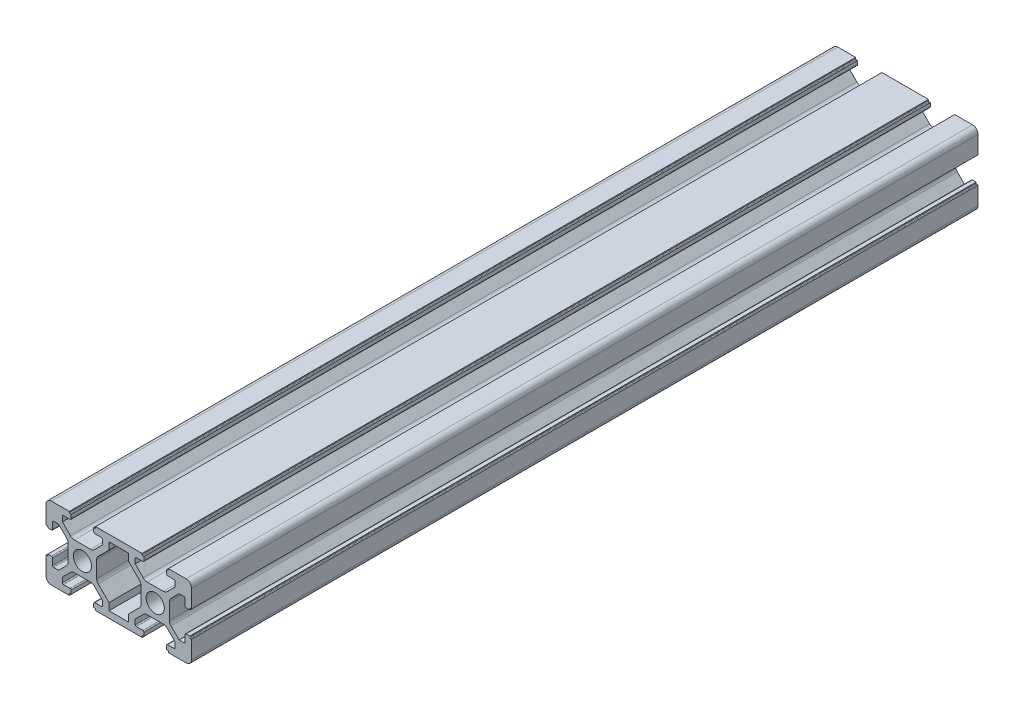
SolidWorks part; units mm, degrees
ref_plane "前视基准面" through (0, 0, 0) normal (0, 0, 1) x (1, 0, 0)
ref_plane "上视基准面" through (0, 0, 0) normal (0, 1, 0) x (1, 0, 0)
ref_plane "右视基准面" through (0, 0, 0) normal (1, 0, 0) x (0, 0, -1)
sketch "草图1" plane through (0, 0, 0) normal (0, 0, 1) x (1, 0, 0)
  line L0 (-1.9716, -6.6942) -> (-4.9322, -3.7335)
  line L1 (-5.3716, -2.6729) -> (-5.3716, 1.7645)
  line L2 (-4.9322, 2.8251) -> (-1.9716, 5.7858)
  line L3 (-0.7716, 9.5458) -> (-5.6716, 9.5458)
  line L4 (-5.6716, 9.5458) -> (-5.6716, 9.2458)
  line L5 (-5.8716, 9.0458) -> (-6.1716, 9.0458)
  line L6 (-6.1716, 9.0458) -> (-6.1716, 8.0458)
  line L7 (-5.8716, 7.7458) -> (-4.0716, 7.7458)
  line L8 (-3.7716, 7.4458) -> (-3.7716, 6.1058)
  line L9 (-3.7716, 6.1058) -> (-5.9922, 3.8851)
  line L10 (-7.0529, 3.4458) -> (-11.4903, 3.4458)
  line L11 (-12.5509, 3.8851) -> (-14.7716, 6.1058)
  line L12 (-14.7716, 6.1058) -> (-14.7716, 7.4458)
  line L13 (-14.4716, 7.7458) -> (-12.6716, 7.7458)
  line L14 (-12.3716, 8.0458) -> (-12.3716, 9.0458)
  line L15 (-12.3716, 9.0458) -> (-12.6716, 9.0458)
  line L16 (-12.8716, 9.2458) -> (-12.8716, 9.5458)
  line L17 (-12.8716, 9.5458) -> (-17.7716, 9.5458)
  line L18 (-19.2716, 8.0458) -> (-19.2716, 3.1458)
  line L19 (-19.2716, 3.1458) -> (-18.9716, 3.1458)
  line L20 (-18.7716, 2.9458) -> (-18.7716, 2.6458)
  line L21 (-18.7716, 2.6458) -> (-17.7716, 2.6458)
  line L22 (-17.4716, 2.9458) -> (-17.4716, 4.7458)
  line L23 (-17.1716, 5.0458) -> (-15.8316, 5.0458)
  line L24 (-15.8316, 5.0458) -> (-13.6109, 2.8251)
  line L25 (-13.1716, 1.7645) -> (-13.1716, -2.6729)
  line L26 (-13.6109, -3.7335) -> (-15.8316, -5.9542)
  line L27 (-15.8316, -5.9542) -> (-17.1716, -5.9542)
  line L28 (-17.4716, -5.6542) -> (-17.4716, -3.8542)
  line L29 (-17.7716, -3.5542) -> (-18.7716, -3.5542)
  line L30 (-18.7716, -3.5542) -> (-18.7716, -3.8542)
  line L31 (-18.9716, -4.0542) -> (-19.2716, -4.0542)
  line L32 (-19.2716, -4.0542) -> (-19.2716, -8.9542)
  line L33 (-17.7716, -10.4542) -> (-12.8716, -10.4542)
  line L34 (-12.8716, -10.4542) -> (-12.8716, -10.1542)
  line L35 (-12.6716, -9.9542) -> (-12.3716, -9.9542)
  line L36 (-12.3716, -9.9542) -> (-12.3716, -8.9542)
  line L37 (-12.6716, -8.6542) -> (-14.4716, -8.6542)
  line L38 (-14.7716, -8.3542) -> (-14.7716, -7.0142)
  line L39 (-14.7716, -7.0142) -> (-12.5509, -4.7935)
  line L40 (-11.4903, -4.3542) -> (-7.0529, -4.3542)
  line L41 (-5.9922, -4.7935) -> (-3.7716, -7.0142)
  line L42 (-3.7716, -7.0142) -> (-3.7716, -8.3542)
  line L43 (-4.0716, -8.6542) -> (-5.8716, -8.6542)
  line L44 (-6.1716, -8.9542) -> (-6.1716, -9.9542)
  line L45 (-6.1716, -9.9542) -> (-5.8716, -9.9542)
  line L46 (-5.6716, -10.1542) -> (-5.6716, -10.4542)
  line L47 (-5.6716, -10.4542) -> (-0.7716, -10.4542)
  line L48 (-0.7716, -10.4542) -> (7.1284, -10.4542)
  line L49 (7.1284, -10.4542) -> (7.1284, -10.1542)
  line L50 (7.3284, -9.9542) -> (7.6284, -9.9542)
  line L51 (7.6284, -9.9542) -> (7.6284, -8.9542)
  line L52 (7.3284, -8.6542) -> (5.5284, -8.6542)
  line L53 (5.2284, -8.3542) -> (5.2284, -7.0142)
  line L54 (5.2284, -7.0142) -> (7.4491, -4.7935)
  line L55 (8.5097, -4.3542) -> (12.9471, -4.3542)
  line L56 (14.0078, -4.7935) -> (16.2284, -7.0142)
  line L57 (16.2284, -7.0142) -> (16.2284, -8.3542)
  line L58 (15.9284, -8.6542) -> (14.1284, -8.6542)
  line L59 (13.8284, -8.9542) -> (13.8284, -9.9542)
  line L60 (13.8284, -9.9542) -> (14.1284, -9.9542)
  line L61 (14.3284, -10.1542) -> (14.3284, -10.4542)
  line L62 (14.3284, -10.4542) -> (19.2284, -10.4542)
  line L63 (20.7284, -8.9542) -> (20.7284, -4.0542)
  line L64 (20.7284, -4.0542) -> (20.4284, -4.0542)
  line L65 (20.2284, -3.8542) -> (20.2284, -3.5542)
  line L66 (20.2284, -3.5542) -> (19.2284, -3.5542)
  line L67 (18.9284, -3.8542) -> (18.9284, -5.6542)
  line L68 (18.6284, -5.9542) -> (17.2884, -5.9542)
  line L69 (17.2884, -5.9542) -> (15.0678, -3.7335)
  line L70 (14.6284, -2.6729) -> (14.6284, 1.7645)
  line L71 (15.0678, 2.8251) -> (17.2884, 5.0458)
  line L72 (17.2884, 5.0458) -> (18.6284, 5.0458)
  line L73 (18.9284, 4.7458) -> (18.9284, 2.9458)
  line L74 (19.2284, 2.6458) -> (20.2284, 2.6458)
  line L75 (20.2284, 2.6458) -> (20.2284, 2.9458)
  line L76 (20.4284, 3.1458) -> (20.7284, 3.1458)
  line L77 (20.7284, 3.1458) -> (20.7284, 8.0458)
  line L78 (19.2284, 9.5458) -> (14.3284, 9.5458)
  line L79 (14.3284, 9.5458) -> (14.3284, 9.2458)
  line L80 (14.1284, 9.0458) -> (13.8284, 9.0458)
  line L81 (13.8284, 9.0458) -> (13.8284, 8.0458)
  line L82 (14.1284, 7.7458) -> (15.9284, 7.7458)
  line L83 (16.2284, 7.4458) -> (16.2284, 6.1058)
  line L84 (16.2284, 6.1058) -> (14.0078, 3.8851)
  line L85 (12.9471, 3.4458) -> (8.5097, 3.4458)
  line L86 (7.4491, 3.8851) -> (5.2284, 6.1058)
  line L87 (5.2284, 6.1058) -> (5.2284, 7.4458)
  line L88 (5.5284, 7.7458) -> (7.3284, 7.7458)
  line L89 (7.6284, 8.0458) -> (7.6284, 9.0458)
  line L90 (7.6284, 9.0458) -> (7.3284, 9.0458)
  line L91 (7.1284, 9.2458) -> (7.1284, 9.5458)
  line L92 (7.1284, 9.5458) -> (2.2284, 9.5458)
  line L93 (3.4284, 5.7858) -> (6.3891, 2.8251)
  line L94 (6.8284, 1.7645) -> (6.8284, -2.6729)
  line L95 (6.3891, -3.7335) -> (3.4284, -6.6942)
  line L96 (-0.7716, 9.5458) -> (2.2284, 9.5458)
  line L99 (-1.9716, 7.7458) -> (3.4284, 7.7458)
  line L100 (3.4284, 7.7458) -> (3.4284, 5.7858)
  line L101 (-1.9716, 7.7458) -> (-1.9716, 5.7858)
  line L102 (-1.9716, -8.6542) -> (3.4284, -8.6542)
  line L103 (3.4284, -8.6542) -> (3.4284, -6.6942)
  line L104 (-1.9716, -8.6542) -> (-1.9716, -6.6942)
  arc A1 (-5.3716, -2.6729) -> (-4.9322, -3.7335) centre (-3.8716, -2.6729) ccw
  arc A2 (-4.9322, 2.8251) -> (-5.3716, 1.7645) centre (-3.8716, 1.7645) ccw
  arc A3 (-5.8716, 9.0458) -> (-5.6716, 9.2458) centre (-5.8716, 9.2458) ccw
  arc A4 (-6.1716, 8.0458) -> (-5.8716, 7.7458) centre (-5.8716, 8.0458) ccw
  arc A5 (-3.7716, 7.4458) -> (-4.0716, 7.7458) centre (-4.0716, 7.4458) ccw
  arc A6 (-7.0529, 3.4458) -> (-5.9922, 3.8851) centre (-7.0529, 4.9458) ccw
  arc A7 (-12.5509, 3.8851) -> (-11.4903, 3.4458) centre (-11.4903, 4.9458) ccw
  arc A8 (-14.4716, 7.7458) -> (-14.7716, 7.4458) centre (-14.4716, 7.4458) ccw
  arc A9 (-12.6716, 7.7458) -> (-12.3716, 8.0458) centre (-12.6716, 8.0458) ccw
  arc A10 (-12.8716, 9.2458) -> (-12.6716, 9.0458) centre (-12.6716, 9.2458) ccw
  arc A11 (-17.7716, 9.5458) -> (-19.2716, 8.0458) centre (-17.7716, 8.0458) ccw
  arc A12 (-18.7716, 2.9458) -> (-18.9716, 3.1458) centre (-18.9716, 2.9458) ccw
  arc A13 (-17.7716, 2.6458) -> (-17.4716, 2.9458) centre (-17.7716, 2.9458) ccw
  arc A14 (-17.1716, 5.0458) -> (-17.4716, 4.7458) centre (-17.1716, 4.7458) ccw
  arc A15 (-13.1716, 1.7645) -> (-13.6109, 2.8251) centre (-14.6716, 1.7645) ccw
  arc A16 (-13.6109, -3.7335) -> (-13.1716, -2.6729) centre (-14.6716, -2.6729) ccw
  arc A17 (-17.4716, -5.6542) -> (-17.1716, -5.9542) centre (-17.1716, -5.6542) ccw
  arc A18 (-17.4716, -3.8542) -> (-17.7716, -3.5542) centre (-17.7716, -3.8542) ccw
  arc A19 (-18.9716, -4.0542) -> (-18.7716, -3.8542) centre (-18.9716, -3.8542) ccw
  arc A20 (-19.2716, -8.9542) -> (-17.7716, -10.4542) centre (-17.7716, -8.9542) ccw
  arc A21 (-12.6716, -9.9542) -> (-12.8716, -10.1542) centre (-12.6716, -10.1542) ccw
  arc A22 (-12.3716, -8.9542) -> (-12.6716, -8.6542) centre (-12.6716, -8.9542) ccw
  arc A23 (-14.7716, -8.3542) -> (-14.4716, -8.6542) centre (-14.4716, -8.3542) ccw
  arc A24 (-11.4903, -4.3542) -> (-12.5509, -4.7935) centre (-11.4903, -5.8542) ccw
  arc A25 (-5.9922, -4.7935) -> (-7.0529, -4.3542) centre (-7.0529, -5.8542) ccw
  arc A26 (-4.0716, -8.6542) -> (-3.7716, -8.3542) centre (-4.0716, -8.3542) ccw
  arc A27 (-5.8716, -8.6542) -> (-6.1716, -8.9542) centre (-5.8716, -8.9542) ccw
  arc A28 (-5.6716, -10.1542) -> (-5.8716, -9.9542) centre (-5.8716, -10.1542) ccw
  arc A29 (7.3284, -9.9542) -> (7.1284, -10.1542) centre (7.3284, -10.1542) ccw
  arc A30 (7.6284, -8.9542) -> (7.3284, -8.6542) centre (7.3284, -8.9542) ccw
  arc A31 (5.2284, -8.3542) -> (5.5284, -8.6542) centre (5.5284, -8.3542) ccw
  arc A32 (8.5097, -4.3542) -> (7.4491, -4.7935) centre (8.5097, -5.8542) ccw
  arc A33 (14.0078, -4.7935) -> (12.9471, -4.3542) centre (12.9471, -5.8542) ccw
  arc A34 (15.9284, -8.6542) -> (16.2284, -8.3542) centre (15.9284, -8.3542) ccw
  arc A35 (14.1284, -8.6542) -> (13.8284, -8.9542) centre (14.1284, -8.9542) ccw
  arc A36 (14.3284, -10.1542) -> (14.1284, -9.9542) centre (14.1284, -10.1542) ccw
  arc A37 (19.2284, -10.4542) -> (20.7284, -8.9542) centre (19.2284, -8.9542) ccw
  arc A38 (20.2284, -3.8542) -> (20.4284, -4.0542) centre (20.4284, -3.8542) ccw
  arc A39 (19.2284, -3.5542) -> (18.9284, -3.8542) centre (19.2284, -3.8542) ccw
  arc A40 (18.6284, -5.9542) -> (18.9284, -5.6542) centre (18.6284, -5.6542) ccw
  arc A41 (14.6284, -2.6729) -> (15.0678, -3.7335) centre (16.1284, -2.6729) ccw
  arc A42 (15.0678, 2.8251) -> (14.6284, 1.7645) centre (16.1284, 1.7645) ccw
  arc A43 (18.9284, 4.7458) -> (18.6284, 5.0458) centre (18.6284, 4.7458) ccw
  arc A44 (18.9284, 2.9458) -> (19.2284, 2.6458) centre (19.2284, 2.9458) ccw
  arc A45 (20.4284, 3.1458) -> (20.2284, 2.9458) centre (20.4284, 2.9458) ccw
  arc A46 (20.7284, 8.0458) -> (19.2284, 9.5458) centre (19.2284, 8.0458) ccw
  arc A47 (14.1284, 9.0458) -> (14.3284, 9.2458) centre (14.1284, 9.2458) ccw
  arc A48 (13.8284, 8.0458) -> (14.1284, 7.7458) centre (14.1284, 8.0458) ccw
  arc A49 (16.2284, 7.4458) -> (15.9284, 7.7458) centre (15.9284, 7.4458) ccw
  arc A50 (12.9471, 3.4458) -> (14.0078, 3.8851) centre (12.9471, 4.9458) ccw
  arc A51 (7.4491, 3.8851) -> (8.5097, 3.4458) centre (8.5097, 4.9458) ccw
  arc A52 (5.5284, 7.7458) -> (5.2284, 7.4458) centre (5.5284, 7.4458) ccw
  arc A53 (7.3284, 7.7458) -> (7.6284, 8.0458) centre (7.3284, 8.0458) ccw
  arc A54 (7.1284, 9.2458) -> (7.3284, 9.0458) centre (7.3284, 9.2458) ccw
  arc A55 (6.8284, 1.7645) -> (6.3891, 2.8251) centre (5.3284, 1.7645) ccw
  arc A56 (6.3891, -3.7335) -> (6.8284, -2.6729) centre (5.3284, -2.6729) ccw
  circle A58 centre (10.7284, -0.4542) radius 2.5
  circle A63 centre (-9.2716, -0.4542) radius 2.5
extrude "凸台-拉伸1" add sketch "草图1" along normal blind 216
